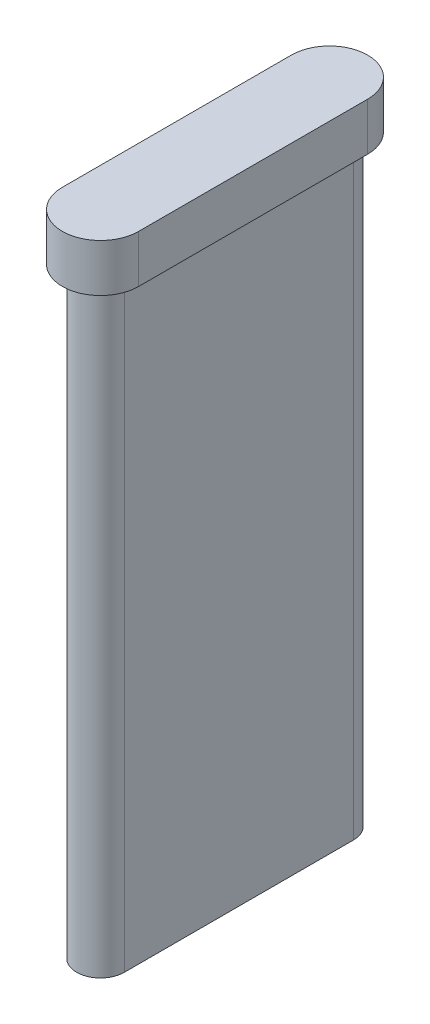
SolidWorks part; units mm, degrees
material "K110"
ref_plane "Front Plane" through (0, 0, 0) normal (0, 0, 1) x (1, 0, 0)
ref_plane "Top Plane" through (0, 0, 0) normal (0, 1, 0) x (1, 0, 0)
ref_plane "Right Plane" through (0, 0, 0) normal (1, 0, 0) x (0, 0, -1)
sketch "Sketch1" plane through (0, 0, 0) normal (0, 1, 0) x (1, 0, 0)
  line L0 (0, -12) -> (0, 12) construction
  line L1 (-2.5, -12) -> (-2.5, 12)
  line L2 (2.5, -12) -> (2.5, 12)
  arc A0 (-2.5, -12) -> (2.5, -12) centre (0, -12) ccw
  arc A1 (2.5, 12) -> (-2.5, 12) centre (0, 12) ccw
  point P2 (0, 0)
  dimension "D2" = 2.5
  dimension "D1" = 24
extrude "Boss-Extrude1" add sketch "Sketch1" against normal blind 68
sketch "Sketch2" plane through (0, 0, 0) normal (0, 1, 0) x (1, 0, 0)
  line L4 (4, -12) -> (4, 12)
  line L5 (-4, 12) -> (-4, -12)
  line L6 (4, -12) -> (4, 12)
  line L7 (-4, 12) -> (-4, -12)
  arc A4 (4, 12) -> (-4, 12) centre (0, 12) ccw
  arc A5 (-4, -12) -> (4, -12) centre (0, -12) ccw
  arc A6 (4, 12) -> (-4, 12) centre (0, 12) ccw
  arc A7 (-4, -12) -> (4, -12) centre (0, -12) ccw
  dimension "D1" = 1.5
extrude "Boss-Extrude2" add sketch "Sketch2" against normal blind 5
